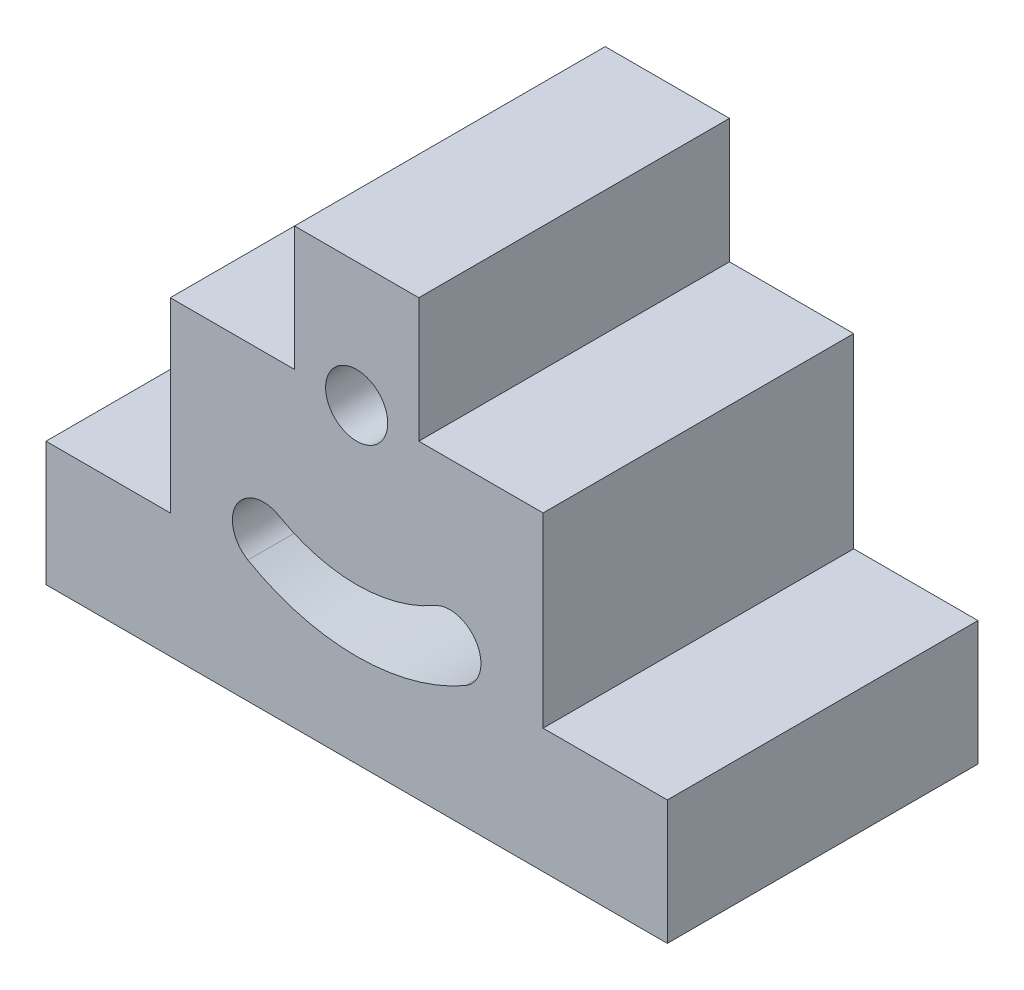
SolidWorks part; units mm, degrees
ref_plane "Front Plane" through (0, 0, 0) normal (0, 0, 1) x (1, 0, 0)
ref_plane "Top Plane" through (0, 0, 0) normal (0, 1, 0) x (1, 0, 0)
ref_plane "Right Plane" through (0, 0, 0) normal (1, 0, 0) x (0, 0, -1)
sketch "Sketch2" plane through (0, 0, 0) normal (0, 0, 1) x (1, 0, 0)
  line L0 (0, 0) -> (0, -5685.7968) construction
  line L1 (0, 0) -> (-5685.7968, 0) construction
  line L2 (-5, 0) -> (5, 0)
  line L3 (5, 0) -> (5, 2)
  line L4 (5, 2) -> (3, 2)
  line L5 (3, 2) -> (3, 5)
  line L6 (3, 5) -> (1, 5)
  line L7 (1, 5) -> (1, 7)
  line L8 (1, 7) -> (-1, 7)
  line L9 (-5, 0) -> (-5, 2)
  line L10 (-1, 5) -> (-1, 7)
  line L11 (-3, 5) -> (-1, 5)
  line L12 (-3, 2) -> (-3, 5)
  line L13 (-5, 2) -> (-3, 2)
  arc A0 (1.5, 2.4019) -> (-1.5, 2.4019) centre (0, 5) cw construction
  circle A5 centre (0, 5) radius 0.5
  arc A6 (-1.75, 1.9689) -> (1.75, 1.9689) centre (0, 5) ccw
  arc A7 (-1.25, 2.8349) -> (1.25, 2.8349) centre (0, 5) ccw
  arc A8 (-1.25, 2.8349) -> (-1.75, 1.9689) centre (-1.5, 2.4019) ccw
  arc A9 (1.75, 1.9689) -> (1.25, 2.8349) centre (1.5, 2.4019) ccw
  point P8 (0, 0)
  point P19 (0, 7)
  point P22 (0, 2)
  point P29 (0, 0)
  point P30 (0, 0)
  point P31 (0, 0)
  dimension "D7" = 1
  dimension "D8" = 3
  dimension "D10" = 0.5
  dimension "D11" = 3
  dimension "D1" = 10
  dimension "D2" = 2
  dimension "D3" = 3
  dimension "D4" = 2
  dimension "D5" = 2
  dimension "D6" = 2
  dimension "D9" = 3
extrude "Boss-Extrude1" add sketch "Sketch2" along normal mid plane 5
